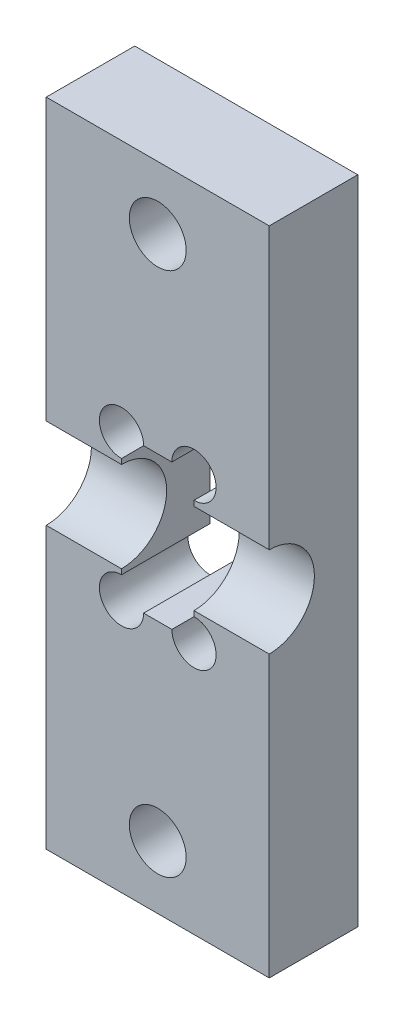
SolidWorks part; units mm, degrees
ref_plane "Top Plane" through (0, 0, 0) normal (0, 0, 1) x (1, 0, 0)
ref_plane "Front Plane" through (0, 0, 0) normal (0, 1, 0) x (1, 0, 0)
ref_plane "Right Plane" through (0, 0, 0) normal (1, 0, 0) x (0, 0, -1)
sketch "Sketch1" plane through (0, 0, 0) normal (0, 0, 1) x (1, 0, 0)
  line L0 (13.25, 24.6944) -> (13.25, 33.7256)
  line L1 (0, 0) -> (20, 0)
  line L2 (0, 0) -> (0, 58.42)
  line L3 (0, 58.42) -> (20, 58.42)
  line L4 (20, 0) -> (20, 58.42)
  line L5 (11.2656, 35.71) -> (8.7344, 35.71)
  line L6 (6.75, 33.7256) -> (6.75, 24.6944)
  line L7 (8.7344, 22.71) -> (11.2656, 22.71)
  line L8 (10, 52.78) -> (10, 5.64) construction
  circle A0 centre (10, 52.78) radius 2.55
  circle A1 centre (10, 5.64) radius 2.55
  arc A4 (13.25, 24.6944) -> (11.2656, 22.71) centre (13.25, 22.71) cw
  arc A5 (8.7344, 22.71) -> (6.75, 24.6944) centre (6.75, 22.71) cw
  arc A6 (6.75, 33.7256) -> (8.7344, 35.71) centre (6.75, 35.71) cw
  arc A7 (13.25, 33.7256) -> (11.2656, 35.71) centre (13.25, 35.71) ccw
  point P22 (13.25, 29.21)
  point P23 (20, 29.21)
  point P24 (10, 35.71)
  point P25 (10, 58.42)
  point P26 (10, 29.21)
  dimension "D1" = 13
  dimension "D3" = 1.9844
  dimension "D4" = 5.1
  dimension "D2" = 6.5
  dimension "D5" = 58.42
  dimension "D6" = 47.14
  dimension "D7" = 20
extrude "Boss-Extrude1" add sketch "Sketch1" along normal blind 7.9375
sketch "Sketch2" plane through (20, 0, 0) normal (1, 0, 0) x (0, 0, -1)
  line L0 (-7.9375, 0) -> (-7.9375, 58.42) construction
  line L1 (-7.9375, 33.26) -> (-7.9375, 25.16)
  arc A0 (-7.9375, 25.16) -> (-7.9375, 33.26) centre (-7.9375, 29.21) ccw
  dimension "D1" = 4.05
extrude "Cut-Extrude1" cut sketch "Sketch2" against normal through all
